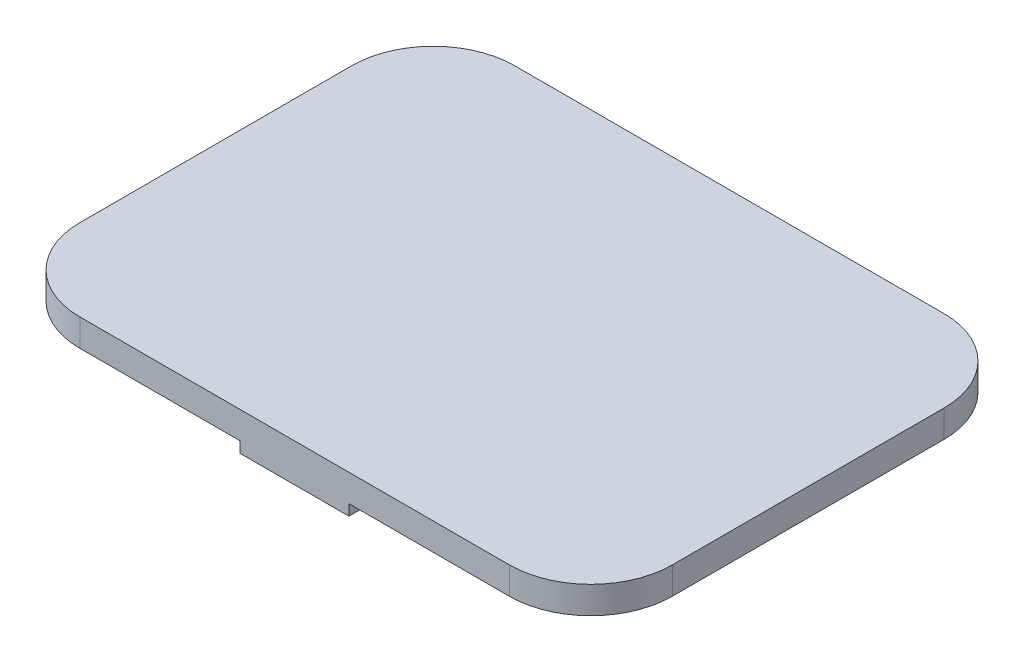
SolidWorks part; units mm, degrees
ref_plane "Front Plane" through (0, 0, 0) normal (0, 0, 1) x (1, 0, 0)
ref_plane "Top Plane" through (0, 0, 0) normal (0, 1, 0) x (1, 0, 0)
ref_plane "Right Plane" through (0, 0, 0) normal (1, 0, 0) x (0, 0, -1)
sketch "Sketch1" plane through (0, 0, 0) normal (0, 1, 0) x (1, 0, 0)
  line L0 (-39.5, 33) -> (39.5, 33)
  line L1 (-39.5, 28) -> (39.5, 28)
  line L2 (-42.5, 25) -> (-42.5, -25)
  line L3 (-39.5, -28) -> (39.5, -28)
  line L4 (42.5, 25) -> (42.5, -25)
  line L5 (-42.5, 28) -> (42.5, -28) construction
  line L6 (-42.5, -28) -> (42.5, 28) construction
  line L7 (47.5, 25) -> (47.5, -25)
  line L8 (-39.5, -33) -> (39.5, -33)
  line L9 (-47.5, 25) -> (-47.5, -25)
  line L10 (-39.5, 40) -> (39.5, 40)
  line L11 (54.5, 25) -> (54.5, -25)
  line L12 (-39.5, -40) -> (39.5, -40)
  line L13 (-54.5, 25) -> (-54.5, -25)
  arc A0 (-42.5, -25) -> (-39.5, -28) centre (-39.5, -25) ccw
  arc A1 (39.5, -28) -> (42.5, -25) centre (39.5, -25) ccw
  arc A2 (39.5, 28) -> (42.5, 25) centre (39.5, 25) cw
  arc A3 (-39.5, 28) -> (-42.5, 25) centre (-39.5, 25) ccw
  arc A4 (39.5, 33) -> (47.5, 25) centre (39.5, 25) cw
  arc A5 (39.5, -33) -> (47.5, -25) centre (39.5, -25) ccw
  arc A6 (-47.5, -25) -> (-39.5, -33) centre (-39.5, -25) ccw
  arc A7 (-39.5, 33) -> (-47.5, 25) centre (-39.5, 25) ccw
  arc A8 (39.5, 40) -> (54.5, 25) centre (39.5, 25) cw
  arc A9 (39.5, -40) -> (54.5, -25) centre (39.5, -25) ccw
  arc A10 (-54.5, -25) -> (-39.5, -40) centre (-39.5, -25) ccw
  arc A11 (-39.5, 40) -> (-54.5, 25) centre (-39.5, 25) ccw
  point P0 (0, 0)
  point P9 (0, 0)
  dimension "D3" = 3
  dimension "D1" = 85
  dimension "D2" = 56
  dimension "D4" = 5
  dimension "D5" = 7
extrude "Boss-Extrude1" add sketch "Sketch1" along normal blind 5 contours L0 A7 L9 A6 L8 A5 L7 A4 A3 L1 A2 L4 A1 L3 A0 L2 | L10 A11 L13 A10 L12 A9 L11 A8 A7 L0 A4 L7 A5 L8 A6 L9
sketch "Sketch2" plane through (0, 0, 0) normal (1, 0, 0) x (0, 0, -1)
  line L0 (-40, 5) -> (-40, 0) construction
  line L1 (-40, 5) -> (-40, 0)
  line L2 (-36.5, -2) -> (-36.5, 0) construction
  line L3 (-40, 0) -> (-33, 0)
  line L4 (-40, 0) -> (-40, -2)
  line L5 (-40, -2) -> (-33, -2)
  line L6 (-33, 0) -> (-33, -2)
  line L7 (-36.5, -1) -> (-36.2, -1) construction
  line L8 (-36.5, -1) -> (-37.5, 0)
  line L9 (-36.5, -1) -> (-37.5, -2)
  line L10 (-36.2, -1) -> (-37.2, 0)
  line L11 (-36.2, -1) -> (-37.2, -2)
  dimension "D1" = 7
  dimension "D2" = 2
  dimension "D3" = 0.3
extrude "Boss-Extrude2" add sketch "Sketch2" along normal blind 10 and the other way blind 10 contours L9 L8 L3 L4 L5
mirror "Mirror1" about plane through (0, 0, 0) normal (0, 0, 1) of "Boss-Extrude2"
